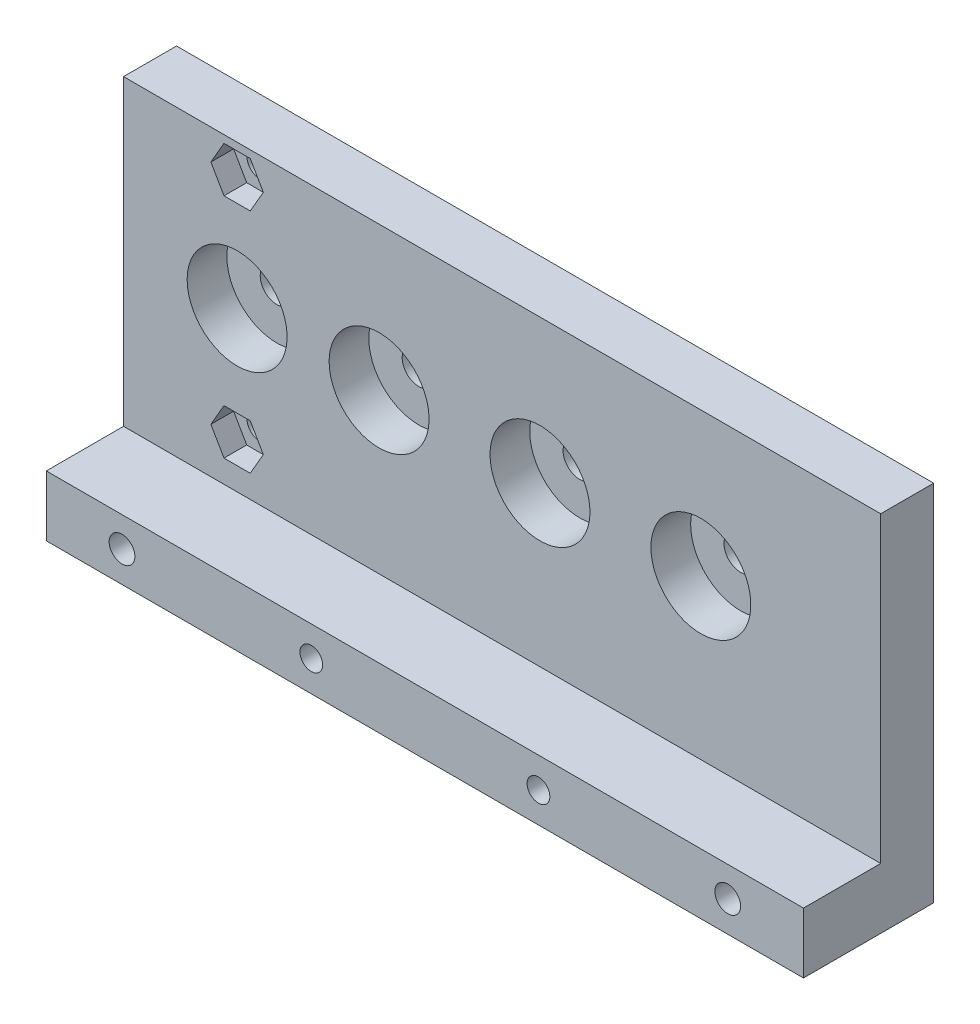
SolidWorks part; units mm, degrees
ref_plane "Front Plane" through (0, 0, 0) normal (0, 0, 1) x (1, 0, 0)
ref_plane "Top Plane" through (0, 0, 0) normal (0, 1, 0) x (1, 0, 0)
ref_plane "Right Plane" through (0, 0, 0) normal (1, 0, 0) x (0, 0, -1)
sketch "Sketch1" plane through (0, 0, 0) normal (0, 0, 1) x (1, 0, 0)
  line L1 (0, 0) -> (100, 0)
  line L2 (0, 0) -> (0, 48)
  line L3 (0, 48) -> (100, 48)
  line L4 (100, 0) -> (100, 48)
  dimension "D1" = 100
  dimension "D2" = 48
extrude "Boss-Extrude1" add sketch "Sketch1" along normal blind 7
sketch "Sketch2" plane through (0, 0, 7) normal (0, 0, 1) x (1, 0, 0)
  line L0 (0, 0) -> (100, 0) construction
  line L1 (0, 48) -> (0, 0) construction
  circle A0 centre (15, 29) radius 2.2
  circle A1 centre (33.75, 29) radius 2.2
  circle A2 centre (55, 29) radius 2.2
  circle A3 centre (76.25, 29) radius 2.2
  dimension "D1" = 4.4
  dimension "D2" = 18.75
  dimension "D3" = 21.25
  dimension "D4" = 21.25
  dimension "D5" = 29
  dimension "D6" = 15
extrude "Cut-Extrude1" cut sketch "Sketch2" against normal up to next
sketch "Sketch3" plane through (0, 0, 0) normal (0, 0, -1) x (-1, 0, 0)
  line L0 (0, 48) -> (0, 0) construction
  line L1 (-100, 0) -> (0, 0)
  line L2 (-100, 0) -> (-100, 8)
  line L3 (-100, 8) -> (0, 8)
  line L4 (0, 0) -> (0, 8)
  dimension "D1" = 8
extrude "Boss-Extrude2" add sketch "Sketch3" along normal blind 10.2
sketch "Sketch4" plane through (0, 0, 0) normal (0, 0, -1) x (-1, 0, 0)
  circle A0 centre (-76.25, 29) radius 6.6
  circle A1 centre (-55, 29) radius 6.6
  circle A2 centre (-33.75, 29) radius 6.6
  circle A3 centre (-15, 29) radius 6.6
  dimension "D1" = 13.2
extrude "Cut-Extrude2" cut sketch "Sketch4" against normal blind 5.25
sketch "Sketch5" plane through (0, 0, 7) normal (0, 0, 1) x (1, 0, 0)
  line L0 (35, 4.0521) -> (65, 4) construction
  line L1 (0, 0) -> (100, 0) construction
  circle A0 centre (35, 4.0521) radius 2.6
  circle A1 centre (65, 4) radius 2.6
  point P6 (50, 0)
  point P7 (50, 4.0261)
  dimension "D1" = 5.2
  dimension "D2" = 30
  dimension "D3" = 4
extrude "Cut-Extrude3" cut sketch "Sketch5" against normal blind 7
sketch "Sketch7" plane through (0, 0, 0) normal (0, 0, 1) x (1, 0, 0)
  circle A0 centre (35, 4.0521) radius 1.5
  circle A1 centre (65, 4) radius 1.5
  dimension "D1" = 3
extrude "Cut-Extrude4" cut sketch "Sketch7" against normal through all
sketch "Sketch8" plane through (0, 0, 7) normal (0, 0, 1) x (1, 0, 0)
  line L0 (10, 4.0521) -> (35, 4.0521) construction
  line L1 (0, 48) -> (0, 0) construction
  line L2 (100, 0) -> (100, 48) construction
  circle A0 centre (10, 4.0521) radius 1.7
  circle A1 centre (90, 4.0521) radius 1.7
  dimension "D1" = 3.4
  dimension "D2" = 10
  dimension "D3" = 10
extrude "Cut-Extrude5" cut sketch "Sketch8" against normal up to next
mirror "Mirror1" about plane through (0, 0, -10.2) normal (0, 0, 1) of bodies 110
delete or keep bodies "Body-Delete/Keep 1" type delete bodies bodies 110
sketch "Sketch9" plane through (0, 0, -27.4) normal (0, 0, -1) x (-1, 0, 0)
  line L1 (-88.2679, 1.0521) -> (-86.5359, 4.0521)
  line L2 (-86.5359, 4.0521) -> (-88.2679, 7.0521)
  line L3 (-88.2679, 7.0521) -> (-91.7321, 7.0521)
  line L4 (-91.7321, 7.0521) -> (-93.4641, 4.0521)
  line L5 (-93.4641, 4.0521) -> (-91.7321, 1.0521)
  line L6 (-91.7321, 1.0521) -> (-88.2679, 1.0521)
  line L7 (-13.4641, 4.0521) -> (-11.7321, 1.0521)
  line L8 (-11.7321, 1.0521) -> (-8.2679, 1.0521)
  line L9 (-8.2679, 1.0521) -> (-6.5359, 4.0521)
  line L10 (-6.5359, 4.0521) -> (-8.2679, 7.0521)
  line L11 (-8.2679, 7.0521) -> (-11.7321, 7.0521)
  line L12 (-11.7321, 7.0521) -> (-13.4641, 4.0521)
  circle A0 centre (-90, 4.0521) radius 3 construction
  circle A1 centre (-10, 4.0521) radius 3 construction
  dimension "D1" = 6
extrude "Cut-Extrude6" cut sketch "Sketch9" against normal blind 3
sketch "Sketch10" plane through (0, 0, -27.4) normal (0, 0, -1) x (-1, 0, 0)
  line L0 (-15, 44) -> (-15, 29) construction
  circle A0 centre (-15, 44) radius 1.7
  circle A1 centre (-15, 14) radius 1.7
  point P6 (0, 0)
  dimension "D1" = 3.4
  dimension "D2" = 30
  dimension "D3" = 15
extrude "Cut-Extrude7" cut sketch "Sketch10" against normal up to next
sketch "Sketch11" plane through (0, 0, -20.4) normal (0, 0, 1) x (1, 0, 0)
  line L1 (18.4641, 44) -> (16.7321, 47)
  line L2 (16.7321, 47) -> (13.2679, 47)
  line L3 (13.2679, 47) -> (11.5359, 44)
  line L4 (11.5359, 44) -> (13.2679, 41)
  line L5 (13.2679, 41) -> (16.7321, 41)
  line L6 (16.7321, 41) -> (18.4641, 44)
  line L7 (18.4641, 14) -> (16.7321, 17)
  line L8 (16.7321, 17) -> (13.2679, 17)
  line L9 (13.2679, 17) -> (11.5359, 14)
  line L10 (11.5359, 14) -> (13.2679, 11)
  line L11 (13.2679, 11) -> (16.7321, 11)
  line L12 (16.7321, 11) -> (18.4641, 14)
  circle A0 centre (15, 44) radius 3 construction
  circle A1 centre (15, 14) radius 3 construction
  dimension "D1" = 6
extrude "Cut-Extrude8" cut sketch "Sketch11" against normal blind 3
